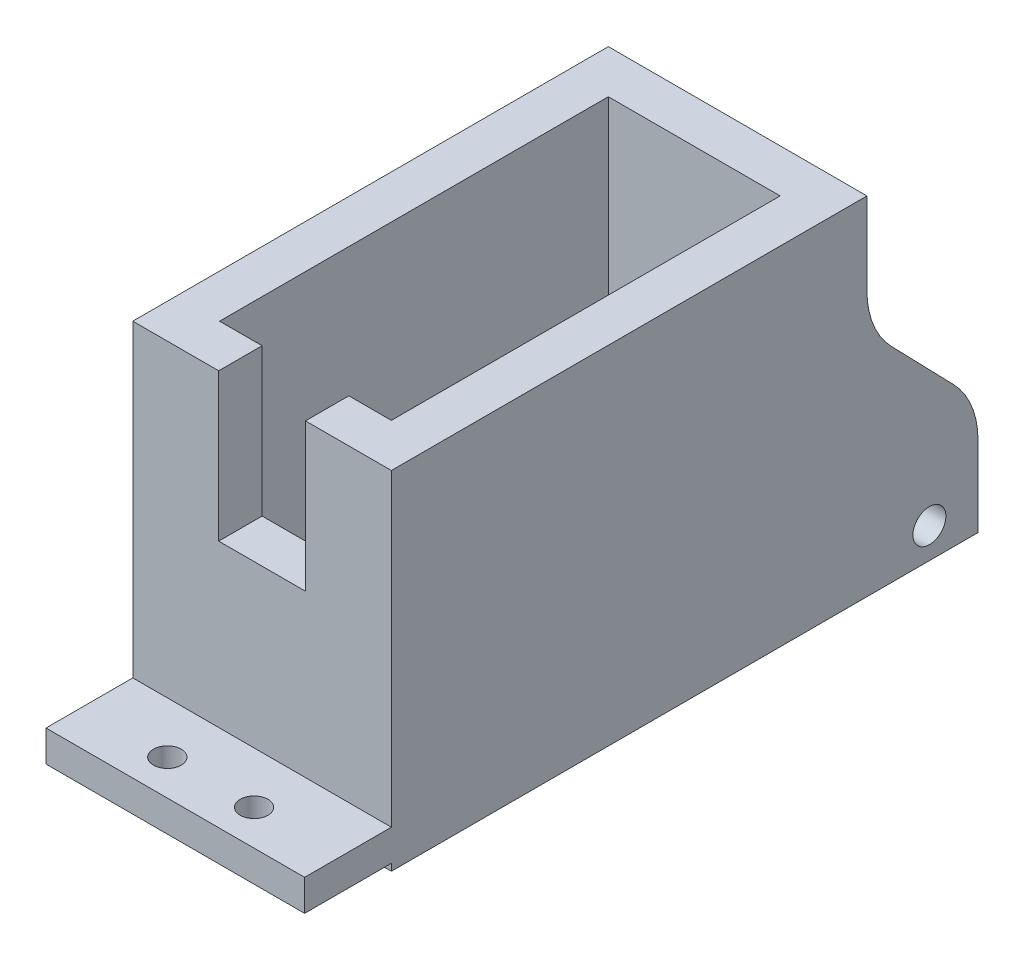
SolidWorks part; units mm, degrees
ref_plane "Front Plane" through (0, 0, 0) normal (0, 0, 1) x (1, 0, 0)
ref_plane "Top Plane" through (0, 0, 0) normal (0, 1, 0) x (1, 0, 0)
ref_plane "Right Plane" through (0, 0, 0) normal (1, 0, 0) x (0, 0, -1)
sketch "Sketch1" plane through (0, 0, 0) normal (0, 1, 0) x (1, 0, 0)
  line L0 (-0.5281, 0.433) -> (-0.5281, -56.463)
  line L1 (-0.5281, -56.463) -> (24.6179, -56.463)
  line L2 (24.6179, -56.463) -> (24.6179, 0.433)
  line L3 (24.6179, 0.433) -> (-0.5281, 0.433)
  line L4 (24.6179, -28.015) -> (30.9679, -28.015)
  line L5 (-0.5281, -28.015) -> (-6.8781, -28.015)
  line L6 (12.0449, 0.433) -> (12.0449, 6.783)
  line L7 (12.0449, 6.783) -> (-6.8781, 6.783)
  line L8 (-6.8781, 6.783) -> (-6.8781, -28.015)
  line L9 (12.0449, -56.463) -> (12.0449, -62.813)
  line L10 (-6.8781, -28.015) -> (-6.8781, -62.813)
  line L11 (-6.8781, -62.813) -> (12.0449, -62.813)
  line L12 (12.0449, -62.813) -> (30.9679, -62.813)
  line L13 (30.9679, -62.813) -> (30.9679, -28.015)
  line L14 (12.0449, 6.783) -> (30.9679, 6.783)
  line L15 (30.9679, 6.783) -> (30.9679, -28.015)
  dimension "D1" = 25.146
  dimension "D2" = 56.896
  dimension "D3" = 6.35
extrude "Boss-Extrude1" add sketch "Sketch1" along normal blind 50.8 contours L10 L11 L9 L1 L0 L5 | L7 L8 L5 L0 L3 L6 | L15 L14 L6 L3 L2 L4 | L12 L13 L4 L2 L1 L9
sketch "Sketch3" plane through (0, 0, 62.813) normal (0, 0, 1) x (1, 0, 0)
  line L0 (12.0449, 0) -> (12.0449, 29.21)
  line L1 (-6.8781, 0) -> (30.9679, 0) construction
  line L2 (12.0449, 29.21) -> (18.3949, 29.21)
  line L3 (18.3949, 29.21) -> (18.3949, 50.8)
  line L4 (-6.8781, 50.8) -> (30.9679, 50.8) construction
  line L5 (18.3949, 50.8) -> (5.6949, 50.8)
  line L6 (5.6949, 50.8) -> (5.6949, 29.21)
  line L7 (5.6949, 29.21) -> (12.0449, 29.21)
  line L8 (5.6949, 50.8) -> (18.3949, 50.8)
  line M6 (30.9679, 50.8) -> (-6.8781, 50.8)
  dimension "D1" = 29.21
  dimension "D2" = 6.35
extrude "Cut-Extrude1" cut sketch "Sketch3" against normal blind 50.8 contours L6 L7 L2 L3 M6
ref_plane "Plane1" through (0, 1.016, 0) normal (0, 1, 0) x (1, 0, 0)
sketch "Sketch5" plane through (0, 1.016, 0) normal (0, 1, 0) x (1, 0, 0)
  line L0 (12.0449, -68.3008) -> (12.0449, -57.3252)
  line L1 (-6.8781, -62.813) -> (30.9679, -62.813) construction
  line L2 (12.0449, -57.3252) -> (5.6949, -57.3252)
  line L3 (12.0449, -57.3252) -> (18.3949, -57.3252)
  line L4 (-6.8781, -75.513) -> (-6.8781, -50.113)
  line L5 (-6.8781, -50.113) -> (30.9679, -50.113)
  line L6 (30.9679, -50.113) -> (30.9679, -75.513)
  line L7 (7.7269, -55.2932) -> (16.3629, -55.2932)
  line L9 (-6.8781, -62.813) -> (30.9679, -62.813)
  line L10 (-6.8781, 6.783) -> (-6.8781, -62.813) construction
  line L11 (5.6949, -62.813) -> (18.3949, -62.813) construction
  line L12 (7.7269, -70.3328) -> (16.3629, -70.3328)
  line L13 (-6.8781, -75.513) -> (30.9679, -75.513)
  line L14 (12.0449, -68.3008) -> (18.3949, -68.3008)
  line L15 (12.0449, -68.3008) -> (5.6949, -68.3008)
  circle A0 centre (5.6949, -55.2932) radius 2.032
  circle A1 centre (18.3949, -55.2932) radius 2.032
  circle A2 centre (18.3949, -70.3328) radius 2.032
  circle A3 centre (5.6949, -70.3328) radius 2.032
  point P18 (0, 0)
  point P32 (12.0449, -62.813)
  dimension "D1" = 4.064
  dimension "D3" = 8.636
  dimension "D4" = 12.7
extrude "Boss-Extrude2" add sketch "Sketch5" along normal blind 4.572
sketch "Sketch8" plane through (30.9679, 0, 0) normal (1, 0, 0) x (0, 0, -1)
  line L0 (6.783, 0) -> (15.927, 0)
  line L1 (6.783, 50.8) -> (6.783, 0) construction
  line L2 (20.8153, 0) -> (-20.8153, 0) construction
  line L3 (15.927, 0) -> (15.927, 4.445)
  line L4 (15.927, 0) -> (23.0375, 0)
  line L5 (23.0375, 0) -> (23.0375, 16.864)
  line L6 (23.0375, 16.864) -> (6.783, 33.6326)
  line L7 (6.783, 33.6326) -> (6.783, 0)
  circle A0 centre (15.927, 4.445) radius 2.413
  dimension "D2" = 4.826
  dimension "D1" = 4.445
  dimension "D3" = 9.144
extrude "Boss-Extrude3" add sketch "Sketch8" against normal up to surface (37.846 mm away)
fillet "Fillet1" radius 12.7 2 edges at (12.0449, 16.864, -23.0375) (12.0449, 33.6326, -6.783)
